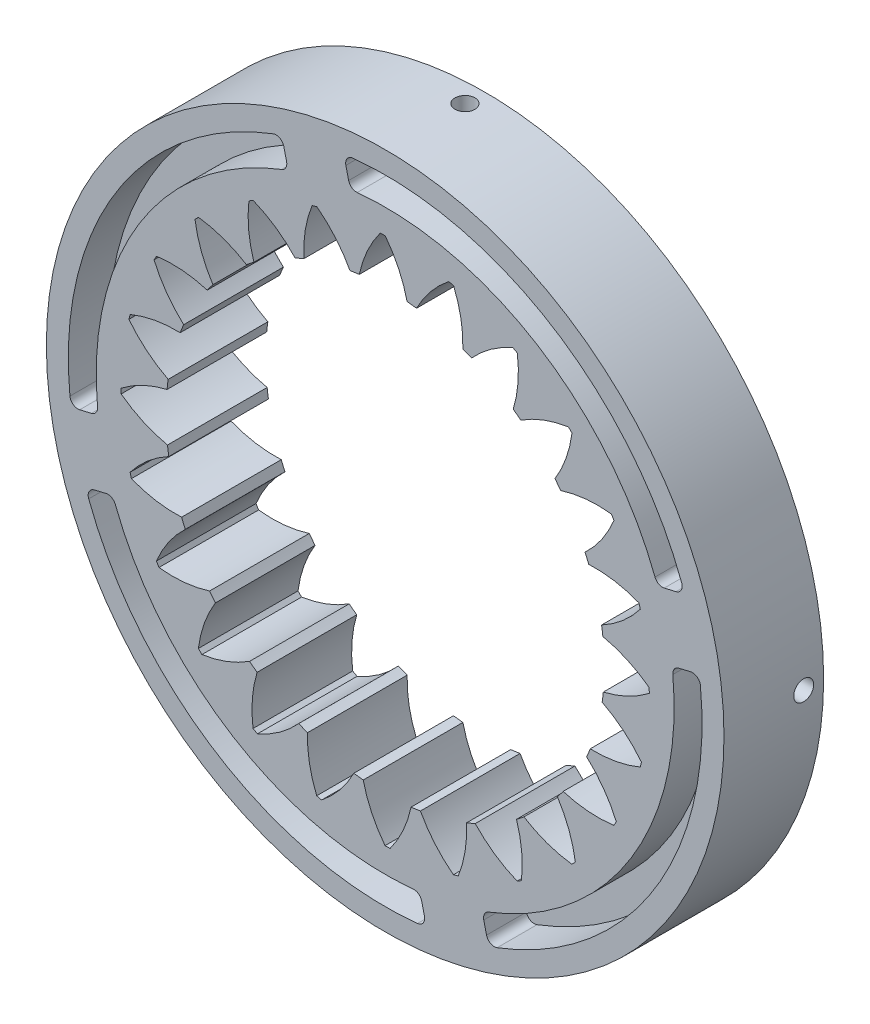
SolidWorks part; units mm, degrees
ref_plane "Front Plane" through (0, 0, 0) normal (0, 0, 1) x (1, 0, 0)
ref_plane "Top Plane" through (0, 0, 0) normal (0, 1, 0) x (1, 0, 0)
ref_plane "Right Plane" through (0, 0, 0) normal (1, 0, 0) x (0, 0, -1)
sketch "Sketch1" plane through (0, 0, 0) normal (0, 1, 0) x (1, 0, 0)
  line L0 (111.4727, 0) -> (26.4727, 0)
  line L1 (26.4727, 0) -> (26.4727, -25)
  line L2 (26.4727, -25) -> (111.4727, -25)
  line L3 (111.4727, -25) -> (111.4727, 0)
  line L4 (26.4727, 0) -> (26.4727, -25) construction
  dimension "D1" = 85
  dimension "D2" = 25
revolve "Revolve1" add sketch "Sketch1" angle 360 about L4
sketch "Sketch2" plane through (0, 0, 0) normal (0, 0, -1) x (-1, 0, 0)
  arc A0 (-3.8799, 50.1455) -> (-6.0595, 51.0715) centre (-26.4727, 0) ccw
  arc A1 (-6.0595, 51.0715) -> (-8.1398, 63.664) centre (-36.0211, 52.59) ccw
  arc A2 (-8.1398, 63.664) -> (-9.3528, 64.0008) centre (-26.4727, 0) ccw
  arc A3 (-9.3528, 64.0008) -> (-17.6283, 54.2842) centre (8.8259, 40.1359) ccw
  arc A4 (-17.6283, 54.2842) -> (-19.9734, 54.6146) centre (-26.4727, 0) ccw
  arc A5 (-19.9734, 54.6146) -> (-25.2419, 66.2396) centre (-49.307, 48.3267) ccw
  arc A6 (-25.2419, 66.2396) -> (-26.5008, 66.251) centre (-26.4727, 0) ccw
  arc A7 (-26.5008, 66.251) -> (-31.9795, 54.7236) centre (-2.7648, 47.9042) ccw
  arc A8 (-31.9795, 54.7236) -> (-34.3301, 54.4358) centre (-26.4727, 0) ccw
  arc A9 (-34.3301, 54.4358) -> (-42.4279, 64.3011) centre (-61.0368, 40.77) ccw
  arc A10 (-42.4279, 64.3011) -> (-43.6469, 63.9863) centre (-26.4727, 0) ccw
  arc A11 (-43.6469, 63.9863) -> (-45.9554, 51.4337) centre (-15.9712, 52.408) ccw
  arc A12 (-45.9554, 51.4337) -> (-48.1514, 50.5473) centre (-26.4727, 0) ccw
  arc A13 (-48.1514, 50.5473) -> (-58.5266, 57.9805) centre (-70.4111, 30.435) ccw
  arc A14 (-58.5266, 57.9805) -> (-59.6225, 57.361) centre (-26.4727, 0) ccw
  arc A15 (-59.6225, 57.361) -> (-58.6035, 44.6386) centre (-29.8932, 53.3402) ccw
  arc A16 (-58.6035, 44.6386) -> (-60.4954, 43.2141) centre (-26.4727, 0) ccw
  arc A17 (-60.4954, 43.2141) -> (-72.4408, 47.7087) centre (-76.7911, 18.0258) ccw
  arc A18 (-72.4408, 47.7087) -> (-73.3391, 46.8266) centre (-26.4727, 0) ccw
  arc A19 (-73.3391, 46.8266) -> (-69.062, 34.8015) centre (-43.5821, 50.6374) ccw
  arc A20 (-69.062, 34.8015) -> (-70.5207, 32.9359) centre (-26.4727, 0) ccw
  arc A21 (-70.5207, 32.9359) -> (-83.2224, 34.1857) centre (-79.742, 4.3882) ccw
  arc A22 (-83.2224, 34.1857) -> (-83.8618, 33.1011) centre (-26.4727, 0) ccw
  arc A23 (-83.8618, 33.1011) -> (-76.6181, 22.5928) centre (-56.105, 44.4837) ccw
  arc A24 (-76.6181, 22.5928) -> (-77.5442, 20.4132) centre (-26.4727, 0) ccw
  arc A25 (-77.5442, 20.4132) -> (-90.1366, 18.3329) centre (-79.0626, -9.5484) ccw
  arc A26 (-90.1366, 18.3329) -> (-90.4735, 17.1199) centre (-26.4727, 0) ccw
  arc A27 (-90.4735, 17.1199) -> (-80.7569, 8.8444) centre (-66.6086, 35.2985) ccw
  arc A28 (-80.7569, 8.8444) -> (-81.0873, 6.4993) centre (-26.4727, 0) ccw
  arc A29 (-81.0873, 6.4993) -> (-92.7122, 1.2308) centre (-74.7994, -22.8343) ccw
  arc A30 (-92.7122, 1.2308) -> (-92.7237, -0.0281) centre (-26.4727, 0) ccw
  arc A31 (-92.7237, -0.0281) -> (-81.1963, -5.5068) centre (-74.3769, 23.7078) ccw
  arc A32 (-81.1963, -5.5068) -> (-80.9085, -7.8575) centre (-26.4727, 0) ccw
  arc A33 (-80.9085, -7.8575) -> (-90.7737, -15.9552) centre (-67.2427, -34.5641) ccw
  arc A34 (-90.7737, -15.9552) -> (-90.4589, -17.1742) centre (-26.4727, 0) ccw
  arc A35 (-90.4589, -17.1742) -> (-77.9064, -19.4827) centre (-78.8806, 10.5015) ccw
  arc A36 (-77.9064, -19.4827) -> (-77.02, -21.6788) centre (-26.4727, 0) ccw
  arc A37 (-77.02, -21.6788) -> (-84.4532, -32.0539) centre (-56.9077, -43.9385) ccw
  arc A38 (-84.4532, -32.0539) -> (-83.8337, -33.1498) centre (-26.4727, 0) ccw
  arc A39 (-83.8337, -33.1498) -> (-71.1113, -32.1308) centre (-79.8129, -3.4205) ccw
  arc A40 (-71.1113, -32.1308) -> (-69.6868, -34.0227) centre (-26.4727, 0) ccw
  arc A41 (-69.6868, -34.0227) -> (-74.1814, -45.9682) centre (-44.4985, -50.3184) ccw
  arc A42 (-74.1814, -45.9682) -> (-73.2993, -46.8664) centre (-26.4727, 0) ccw
  arc A43 (-73.2993, -46.8664) -> (-61.2742, -42.5893) centre (-77.1101, -17.1094) ccw
  arc A44 (-61.2742, -42.5893) -> (-59.4086, -44.048) centre (-26.4727, 0) ccw
  arc A45 (-59.4086, -44.048) -> (-60.6583, -56.7498) centre (-30.8609, -53.2693) ccw
  arc A46 (-60.6583, -56.7498) -> (-59.5738, -57.3891) centre (-26.4727, 0) ccw
  arc A47 (-59.5738, -57.3891) -> (-49.0655, -50.1455) centre (-70.9564, -29.6323) ccw
  arc A48 (-49.0655, -50.1455) -> (-46.8858, -51.0715) centre (-26.4727, 0) ccw
  arc A49 (-46.8858, -51.0715) -> (-44.8056, -63.664) centre (-16.9243, -52.59) ccw
  arc A50 (-44.8056, -63.664) -> (-43.5925, -64.0008) centre (-26.4727, 0) ccw
  arc A51 (-43.5925, -64.0008) -> (-35.317, -54.2842) centre (-61.7712, -40.1359) ccw
  arc A52 (-35.317, -54.2842) -> (-32.972, -54.6146) centre (-26.4727, 0) ccw
  arc A53 (-32.972, -54.6146) -> (-27.7035, -66.2396) centre (-3.6384, -48.3267) ccw
  arc A54 (-27.7035, -66.2396) -> (-26.4446, -66.251) centre (-26.4727, 0) ccw
  arc A55 (-26.4446, -66.251) -> (-20.9659, -54.7236) centre (-50.1805, -47.9042) ccw
  arc A56 (-20.9659, -54.7236) -> (-18.6152, -54.4358) centre (-26.4727, 0) ccw
  arc A57 (-18.6152, -54.4358) -> (-10.5175, -64.3011) centre (8.0915, -40.77) ccw
  arc A58 (-10.5175, -64.3011) -> (-9.2985, -63.9863) centre (-26.4727, 0) ccw
  arc A59 (-9.2985, -63.9863) -> (-6.99, -51.4337) centre (-36.9742, -52.408) ccw
  arc A60 (-6.99, -51.4337) -> (-4.7939, -50.5473) centre (-26.4727, 0) ccw
  arc A61 (-4.7939, -50.5473) -> (5.5812, -57.9805) centre (17.4658, -30.435) ccw
  arc A62 (5.5812, -57.9805) -> (6.6772, -57.361) centre (-26.4727, 0) ccw
  arc A63 (6.6772, -57.361) -> (5.6582, -44.6386) centre (-23.0522, -53.3402) ccw
  arc A64 (5.6582, -44.6386) -> (7.55, -43.2141) centre (-26.4727, 0) ccw
  arc A65 (7.55, -43.2141) -> (19.4955, -47.7087) centre (23.8458, -18.0258) ccw
  arc A66 (19.4955, -47.7087) -> (20.3937, -46.8266) centre (-26.4727, 0) ccw
  arc A67 (20.3937, -46.8266) -> (16.1167, -34.8015) centre (-9.3633, -50.6374) ccw
  arc A68 (16.1167, -34.8015) -> (17.5753, -32.9359) centre (-26.4727, 0) ccw
  arc A69 (17.5753, -32.9359) -> (30.2771, -34.1857) centre (26.7966, -4.3882) ccw
  arc A70 (30.2771, -34.1857) -> (30.9164, -33.1011) centre (-26.4727, 0) ccw
  arc A71 (30.9164, -33.1011) -> (23.6728, -22.5928) centre (3.1597, -44.4837) ccw
  arc A72 (23.6728, -22.5928) -> (24.5989, -20.4132) centre (-26.4727, 0) ccw
  arc A73 (24.5989, -20.4132) -> (37.1913, -18.3329) centre (26.1173, 9.5484) ccw
  arc A74 (37.1913, -18.3329) -> (37.5281, -17.1199) centre (-26.4727, 0) ccw
  arc A75 (37.5281, -17.1199) -> (27.8116, -8.8444) centre (13.6632, -35.2985) ccw
  arc A76 (27.8116, -8.8444) -> (28.142, -6.4993) centre (-26.4727, 0) ccw
  arc A77 (28.142, -6.4993) -> (39.7669, -1.2308) centre (21.854, 22.8343) ccw
  arc A78 (39.7669, -1.2308) -> (39.7783, 0.0281) centre (-26.4727, 0) ccw
  arc A79 (39.7783, 0.0281) -> (28.2509, 5.5068) centre (21.4315, -23.7078) ccw
  arc A80 (28.2509, 5.5068) -> (27.9632, 7.8575) centre (-26.4727, 0) ccw
  arc A81 (27.9632, 7.8575) -> (37.8284, 15.9552) centre (14.2974, 34.5641) ccw
  arc A82 (37.8284, 15.9552) -> (37.5136, 17.1742) centre (-26.4727, 0) ccw
  arc A83 (37.5136, 17.1742) -> (24.961, 19.4827) centre (25.9353, -10.5015) ccw
  arc A84 (24.961, 19.4827) -> (24.0746, 21.6788) centre (-26.4727, 0) ccw
  arc A85 (24.0746, 21.6788) -> (31.5079, 32.0539) centre (3.9623, 43.9385) ccw
  arc A86 (31.5079, 32.0539) -> (30.8883, 33.1498) centre (-26.4727, 0) ccw
  arc A87 (30.8883, 33.1498) -> (18.166, 32.1308) centre (26.8675, 3.4205) ccw
  arc A88 (18.166, 32.1308) -> (16.7414, 34.0227) centre (-26.4727, 0) ccw
  arc A89 (16.7414, 34.0227) -> (21.2361, 45.9682) centre (-8.4468, 50.3184) ccw
  arc A90 (21.2361, 45.9682) -> (20.354, 46.8664) centre (-26.4727, 0) ccw
  arc A91 (20.354, 46.8664) -> (8.3289, 42.5893) centre (24.1647, 17.1094) ccw
  arc A92 (8.3289, 42.5893) -> (6.4632, 44.048) centre (-26.4727, 0) ccw
  arc A93 (6.4632, 44.048) -> (7.713, 56.7498) centre (-22.0844, 53.2693) ccw
  arc A94 (7.713, 56.7498) -> (6.6285, 57.3891) centre (-26.4727, 0) ccw
  arc A95 (6.6285, 57.3891) -> (-3.8799, 50.1455) centre (18.011, 29.6323) ccw
extrude "Cut-Extrude1" cut sketch "Sketch2" against normal through all
sketch "Sketch3" plane through (0, 0, 0) normal (0, 0, -1) x (-1, 0, 0)
  line L0 (-34.9727, -78.25) -> (-18.4727, -78.25)
  line L1 (-18.4727, -78.25) -> (-18.4727, -71.75)
  line L2 (-18.4727, -71.75) -> (-34.9727, -71.75)
  line L3 (-34.9727, -71.75) -> (-34.9727, -78.25)
  line L4 (-34.9727, -75) -> (-18.4727, -75) construction
  line L5 (-98.2227, -8) -> (-98.2227, 8.5)
  line L6 (-98.2227, 8.5) -> (-104.7227, 8.5)
  line L7 (-104.7227, 8.5) -> (-104.7227, -8)
  line L8 (-104.7227, -8) -> (-98.2227, -8)
  line L9 (-34.4727, 71.75) -> (-17.9727, 71.75)
  line L10 (-17.9727, 71.75) -> (-17.9727, 78.25)
  line L11 (-17.9727, 78.25) -> (-34.4727, 78.25)
  line L12 (-34.4727, 78.25) -> (-34.4727, 71.75)
  line L13 (45.2773, 8) -> (45.2773, -8.5)
  line L14 (45.2773, -8.5) -> (51.7773, -8.5)
  line L15 (51.7773, -8.5) -> (51.7773, 8)
  line L16 (51.7773, 8) -> (45.2773, 8)
  circle A0 centre (-26.4727, 0) radius 85 construction
  circle A1 centre (-26.4727, 0) radius 85 construction
  circle A2 centre (-26.4727, 0) radius 75 construction
  dimension "D5" = 150
  dimension "D6" = 4
  dimension "D7" = 170
  dimension "D1" = 6.5
  dimension "D2" = 16.5
  dimension "D3" = 8
  dimension "D4" = 75
extrude "Cut-Extrude2" cut sketch "Sketch3" against normal blind 10
sketch "Sketch11" plane through (0, 0, 25) normal (0, 0, 1) x (1, 0, 0)
  circle A0 centre (26.4727, 0) radius 85 construction
  circle A2 centre (26.4727, 0) radius 85
  line B0 (26.4727, 0) -> (109.1875, 19.5771) construction
  line B1 (26.4727, 0) -> (46.0498, -82.7148) construction
  line B2 (101.6205, 25.9433) -> (94.7693, 24.3274)
  line B3 (0.5294, 75.1478) -> (2.1453, 68.2966)
  line B4 (105.2934, 10.3705) -> (98.4422, 8.7547)
  line B5 (16.1022, 78.8207) -> (17.718, 71.9695)
  line B6 (50.8001, -68.2966) -> (52.4159, -75.1478)
  line B7 (35.2273, -71.9695) -> (36.8432, -78.8207)
  line B8 (-41.8239, -24.3274) -> (-48.6752, -25.9433)
  line B9 (-45.4968, -8.7547) -> (-52.348, -10.3705)
  arc B10 (101.6205, 25.9433) -> (16.1022, 78.8207) centre (26.4727, 0) ccw
  arc B11 (94.7693, 24.3274) -> (17.718, 71.9695) centre (26.4727, 0) ccw
  arc B12 (50.8001, -68.2966) -> (98.4422, 8.7547) centre (26.4727, 0) ccw
  arc B13 (52.4159, -75.1478) -> (105.2934, 10.3705) centre (26.4727, 0) ccw
  arc B14 (2.1453, 68.2966) -> (-45.4968, -8.7547) centre (26.4727, 0) ccw
  arc B15 (0.5294, 75.1478) -> (-52.348, -10.3705) centre (26.4727, 0) ccw
  arc B16 (-41.8239, -24.3274) -> (35.2273, -71.9695) centre (26.4727, 0) ccw
  arc B17 (-48.6752, -25.9433) -> (36.8432, -78.8207) centre (26.4727, 0) ccw
  circle B18 centre (26.4727, 0) radius 79.5 construction
sketch_block_instance "Block1-2"
sketch_block "Block1" parameters "D1"=159, "D2"=7, "D3"=16, "D4"=16, "D5"=16, "D6"=8, "D7"=8, "D8"=8, "D9"=0.045, "D10"=90, "D11"=90
extrude "Cut-Extrude10" cut sketch "Sketch11" against normal blind 10 contours B3 B15 B9 B14 | B11 B2 B10 B5 | B6 B13 B4 B12 | B8 B17 B7 B16
fillet "Fillet2" radius 2 16 edges at (-45.4968, -8.7547, 20) (-52.348, -10.3705, 20) (2.1453, 68.2966, 20) (0.5294, 75.1478, 20) (16.1022, 78.8207, 20) (17.718, 71.9695, 20) (101.6205, 25.9433, 20) (94.7693, 24.3274, 20) (105.2934, 10.3705, 20) (98.4422, 8.7547, 20) (52.4159, -75.1478, 20) (50.8001, -68.2966, 20) (36.8432, -78.8207, 20) (35.2273, -71.9695, 20) (-41.8239, -24.3274, 20) (-48.6752, -25.9433, 20)
ref_plane "Plane1" through (95, 0, 0) normal (1, 0, 0) x (0, 0, -1)
sketch "Sketch12" plane through (95, 0, 0) normal (1, 0, 0) x (0, 0, -1)
  circle A0 centre (-5, 0) radius 2.5
  dimension "D1" = 5
  dimension "D2" = 5
extrude "Cut-Extrude11" cut sketch "Sketch12" along normal through all
pattern_circular "CirPattern1" count 4 over 360 about axis through (26.4727, 0, 0) along (0, 0, 1) of "Cut-Extrude11"
sketch "Sketch14" plane through (0, 0, 25) normal (0, 0, 1) x (1, 0, 0)
  line L0 (30.8144, 59.8427) -> (30.8144, 53.6633) construction
  line L1 (26.4727, 0) -> (26.4727, 59.563) construction
  line L2 (26.4727, 0) -> (17.5541, 67.7429) construction
  line L3 (3.2006, 48.1174) -> (57.3684, 55.2488) construction
  circle A0 centre (26.4727, 0) radius 60 construction
  circle A1 centre (26.4727, 0) radius 66.251 construction
  circle A2 centre (26.4727, 0) radius 50.7434 construction
  circle A3 centre (26.4727, 0) radius 54.9746 construction
  arc A4 (32.4818, 54.6452) -> (27.1022, 66.248) centre (3.2006, 48.1174) ccw
  arc A5 (32.4818, 54.6452) -> (20.4635, 54.6452) centre (26.4727, 0) ccw
  arc A6 (27.1022, 66.248) -> (25.8432, 66.248) centre (26.4727, 0) ccw
  arc A7 (25.8432, 66.248) -> (20.4635, 54.6452) centre (49.7447, 48.1174) ccw
  circle A8 centre (26.4727, 0) radius 85 construction
  dimension "D1" = 120
  dimension "D2" = 101.4868
  dimension "D3" = 132.502
  dimension "D4" = 109.9492
  dimension "D6" = 30
  dimension "D5" = 7.5
  dimension "D7" = 4.3417
